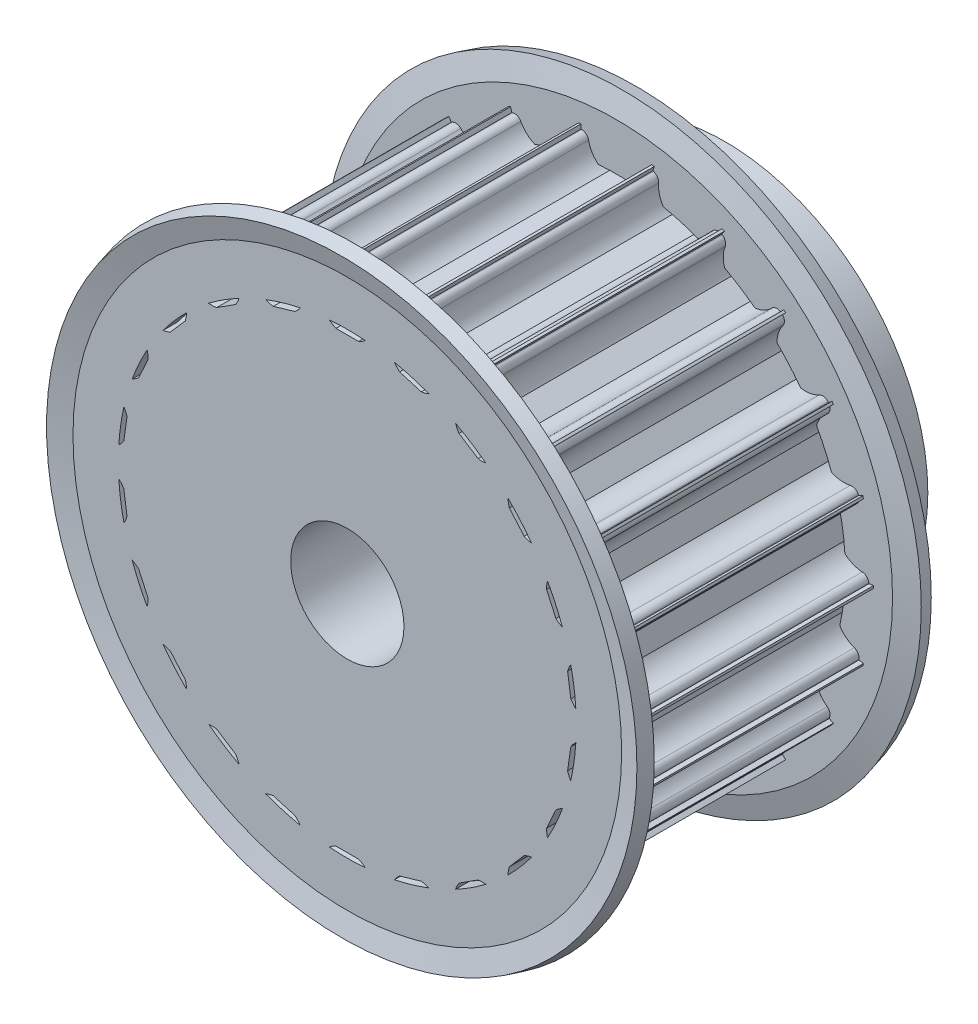
SolidWorks part; units mm, degrees
ref_plane "Front Plane" through (0, 0, 0) normal (0, 0, 1) x (1, 0, 0)
ref_plane "Top Plane" through (0, 0, 0) normal (0, 1, 0) x (1, 0, 0)
ref_plane "Right Plane" through (0, 0, 0) normal (1, 0, 0) x (0, 0, -1)
ref_axis "Axis1" through (0, 0, 55) along (0, 0, -1)
sketch "Sketch1" plane through (0, 0, 0) normal (1, 0, 0) x (0, 0, -1)
  line L0 (0, 6) -> (0, 27.25)
  line L1 (0, 27.25) -> (30, 27.25)
  line L2 (30, 27.25) -> (30, 21.5)
  line L3 (30, 21.5) -> (40, 21.5)
  line L4 (40, 21.5) -> (40, 6)
  line L5 (40, 6) -> (0, 6)
  dimension "D1" = 6
  dimension "D2" = 21.25
  dimension "D3" = 30
  dimension "D4" = 10
  dimension "D5" = 15.5
revolve "Revolve1" add sketch "Sketch1" angle 360 about axis through (0, 0, 55) along (0, 0, -1)
sketch "Sketch2" plane through (0, 0, 0) normal (0, 0, 1) x (1, 0, 0)
  line L0 (3.6742, 26.5) -> (3.75, 26.5)
  line L1 (-3.75, 28.5) -> (3.75, 28.5)
  line L2 (-3.75, 28.5) -> (-3.75, 26.5)
  line L3 (-3.75, 26.5) -> (-3.6742, 26.5)
  line L4 (3.75, 28.5) -> (3.75, 26.5)
  line L5 (1.199, 23.75) -> (-1.199, 23.75)
  arc A0 (2.9394, 25.9) -> (1.199, 23.75) centre (0, 26.5) cw
  arc A1 (2.9394, 25.9) -> (3.6742, 26.5) centre (3.6742, 25.75) cw
  arc A2 (-2.9394, 25.9) -> (-3.6742, 26.5) centre (-3.6742, 25.75) ccw
  arc A3 (-1.199, 23.75) -> (-2.9394, 25.9) centre (0, 26.5) cw
  point P11 (3, 26.5)
  point P14 (-3, 26.5)
  dimension "D1" = 3
  dimension "D5" = 0.75
  dimension "D2" = 2
  dimension "D3" = 7.5
  dimension "D4" = 26.5
  dimension "D6" = 2.75
extrude "Cut-Extrude1" cut sketch "Sketch2" against normal through all
pattern_circular "CirPattern1" count 22 over 360 about axis through (0, 0, 0) along (0, 0, 1) of "Cut-Extrude1"
sketch "Sketch3" plane through (0, 0, 0) normal (1, 0, 0) x (0, 0, -1)
  line L0 (0, 25.679) -> (0, 23.1257) construction
  line L1 (0, 24.2607) -> (1.5, 24.2607)
  line L2 (0, 24.2607) -> (0, 29.2607)
  line L3 (0, 29.2607) -> (1.5, 29.2607)
  line L4 (1.5, 24.2607) -> (1.5, 29.2607)
  line L5 (1.5, 29.2607) -> (0.0511, 28.8724) construction
  line L6 (1.5, 29.2607) -> (0.8569, 31.6607)
  line L7 (0.0511, 28.8724) -> (-0.592, 31.2724)
  line L8 (0.8569, 31.6607) -> (-0.592, 31.2724)
  line L9 (15, 26.9539) -> (15, -33.4204) construction
  line L10 (0, 26.9539) -> (30, 26.9539) construction
  line L11 (28.5, 29.2607) -> (29.9489, 28.8724) construction
  line L12 (29.1431, 31.6607) -> (30.592, 31.2724)
  line L13 (29.9489, 28.8724) -> (30.592, 31.2724)
  line L14 (28.5, 29.2607) -> (29.1431, 31.6607)
  line L15 (28.5, 24.2607) -> (28.5, 29.2607)
  line L16 (30, 29.2607) -> (28.5, 29.2607)
  line L17 (30, 24.2607) -> (30, 29.2607)
  line L18 (30, 24.2607) -> (28.5, 24.2607)
  dimension "D1" = 1.5
  dimension "D2" = 5
  dimension "D3" = 1.5
  dimension "D4" = 2.4
  dimension "D5" = 165
revolve "Revolve2" add sketch "Sketch3" angle 360 about axis through (0, 0, 55) along (0, 0, -1)
